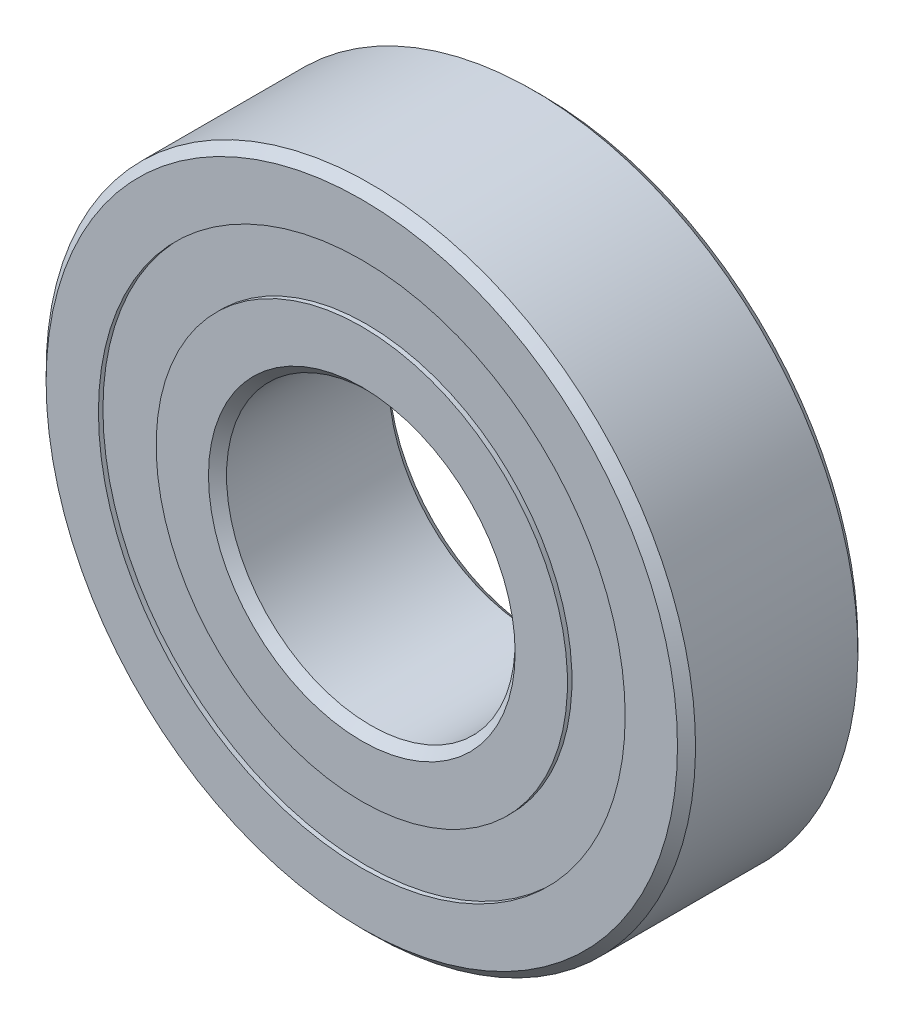
SolidWorks part; units mm, degrees
ref_plane "Front Plane" through (0, 0, 0) normal (0, 0, 1) x (1, 0, 0)
ref_plane "Top Plane" through (0, 0, 0) normal (0, 1, 0) x (1, 0, 0)
ref_plane "Right Plane" through (0, 0, 0) normal (1, 0, 0) x (0, 0, -1)
sketch "Sketch1" plane through (0, 0, 0) normal (0, 0, 1) x (1, 0, 0)
  line L0 (-14.2875, 0) -> (14.2875, 0) construction
  line L1 (-6.35, 0) -> (6.35, 0) construction
  circle A0 centre (0, 0) radius 6.35 construction
  circle A1 centre (0, 0) radius 14.2875 construction
  point P3 (0, 0)
  point P6 (0, 0)
  point P7 (0, -6.35)
  point P11 (0, -14.2875)
  point P12 (0, 6.35)
  point P13 (0, 14.2875)
  dimension "OD" = 28.575
  dimension "ID" = 12.7
sketch "Sketch2" plane through (0, 0, 0) normal (1, 0, 0) x (0, 0, -1)
  line L0 (-3.9687, 14.2875) -> (3.9688, 14.2875) construction
  line L1 (0, 14.2875) -> (0, -14.2875) construction
  line L2 (3.5719, 14.2875) -> (-3.5719, 14.2875)
  line L3 (-3.5719, 14.2875) -> (-3.9687, 13.8906)
  line L4 (-3.9687, 13.8906) -> (-3.9687, 11.5887)
  line L5 (-3.9687, 11.5887) -> (-1.7639, 11.5887)
  line L6 (3.9688, 11.5887) -> (1.7639, 11.5887)
  line L7 (3.9688, 13.8906) -> (3.9688, 11.5887)
  line L8 (3.5719, 14.2875) -> (3.9688, 13.8906)
  line L9 (0, 14.2875) -> (0, 10.3188) construction
  line L10 (0, 10.3188) -> (0, 6.35) construction
  line L11 (0, 14.2875) -> (0, -14.2875) construction
  line L12 (-3.9688, 0) -> (3.9688, 0) construction
  line L13 (3.9688, 6.35) -> (-3.9687, 6.35) construction
  line L14 (-3.9687, 6.35) -> (-3.9687, -6.35) construction
  line L15 (-3.9688, -6.35) -> (3.9687, -6.35) construction
  line L16 (3.9687, 14.2875) -> (3.9687, -14.2875) construction
  arc A0 (-1.7639, 11.5887) -> (1.7639, 11.5887) centre (0, 10.3188) cw
  circle A1 centre (0, 10.3188) radius 2.1735 construction
  point P14 (0, 6.35)
  point P17 (0, 0)
  point P21 (0, 14.2875)
  point P29 (0, 6.35)
  point P30 (0, -6.35)
  dimension "Width" = 7.9375
  dimension "D1" = 45
  dimension "D2" = 0.3969
  dimension "D3" = 3.5278
  dimension "D4" = 1.27
  dimension "For Shaft Diameter" = 12.7
  dimension "For Housing ID" = 28.575
sketch "Sketch3" plane through (0, 0, 0) normal (1, 0, 0) x (0, 0, -1)
  line L0 (3.5719, 14.2875) -> (3.9688, 13.8906) construction
  line L1 (3.9688, 13.8906) -> (3.9688, 11.5887) construction
  line L2 (3.9688, 11.5887) -> (1.7639, 11.5887) construction
  line L3 (-3.9687, 11.5887) -> (-1.7639, 11.5887) construction
  line L4 (-3.9687, 13.8906) -> (-3.9687, 11.5887) construction
  line L5 (-3.5719, 14.2875) -> (-3.9687, 13.8906) construction
  line L6 (3.5719, 14.2875) -> (-3.5719, 14.2875) construction
  line L7 (3.5719, 14.2875) -> (3.9688, 13.8906)
  line L8 (3.9688, 13.8906) -> (3.9688, 11.5887)
  line L9 (3.9688, 11.5887) -> (1.7639, 11.5887)
  line L10 (-3.9687, 11.5887) -> (-1.7639, 11.5887)
  line L11 (-3.9687, 13.8906) -> (-3.9687, 11.5887)
  line L12 (-3.5719, 14.2875) -> (-3.9687, 13.8906)
  line L13 (3.5719, 14.2875) -> (-3.5719, 14.2875)
  arc A0 (1.7639, 11.5887) -> (-1.7639, 11.5887) centre (0, 10.3188) ccw construction
  arc A1 (1.7639, 11.5887) -> (-1.7639, 11.5887) centre (0, 10.3188) ccw
revolve "Revolve1" add sketch "Sketch3" angle 360 about L12
sketch "Sketch4" plane through (0, 0, 0) normal (1, 0, 0) x (0, 0, -1)
  line L0 (0, 14.2875) -> (0, -14.2875) construction
  line L1 (0, 14.2875) -> (0, -14.2875) construction
  line L2 (-3.5719, 6.35) -> (-3.9688, 6.7469)
  line L3 (-3.9688, 6.7469) -> (-3.9688, 9.0488)
  line L5 (-3.9688, 9.0488) -> (-1.7639, 9.0488)
  line L6 (-3.5719, 6.35) -> (3.5719, 6.35)
  line L8 (3.5719, 6.35) -> (3.9688, 6.7469)
  line L10 (3.9688, 6.7469) -> (3.9688, 9.0488)
  line L11 (3.9688, 9.0488) -> (1.7639, 9.0488)
  line L12 (-3.9687, 13.8906) -> (-3.9687, 11.5887) construction
  line L13 (3.5719, 14.2875) -> (3.9688, 13.8906) construction
  line L15 (3.9688, -13.8906) -> (3.9688, 13.8906) construction
  line L16 (3.5719, 14.2875) -> (3.5719, -14.2875) construction
  arc A1 (1.7639, 9.0488) -> (-1.7639, 9.0488) centre (0, 10.3188) cw
  circle A2 centre (0, 10.3188) radius 2.1735 construction
  point P1 (0, 6.35)
revolve "Revolve2" add sketch "Sketch4" angle 360 about L12
sketch "Sketch5" plane through (0, 0, 0) normal (1, 0, 0) x (0, 0, -1)
  line L0 (-2.1735, 10.3188) -> (2.1735, 10.3188)
  arc A2 (-2.1735, 10.3188) -> (2.1735, 10.3188) centre (0, 10.3188) cw
  arc A3 (1.7639, 11.5887) -> (-1.7639, 11.5887) centre (0, 10.3188) ccw construction
revolve "Revolve3" add sketch "Sketch5" angle 360 about L0
pattern_circular "CirPattern1" count 8 over 360 about axis through (0, 0, 0) along (0, 0, 1) of bodies 104
sketch "Sketch6" plane through (0, 0, 0) normal (1, 0, 0) x (0, 0, -1)
  line L0 (-3.9687, 11.5887) -> (-1.7639, 11.5887) construction
  line L1 (-3.7703, 11.5887) -> (-2.1735, 11.5887)
  line L2 (-3.7703, 11.5887) -> (-3.7703, 9.0488)
  line L3 (-3.7703, 9.0488) -> (-2.1735, 9.0488)
  line L4 (-2.1735, 11.5887) -> (-2.1735, 9.0488)
  line L5 (-3.9688, 9.0488) -> (-1.7639, 9.0488) construction
  line L6 (-3.5719, 14.2875) -> (-3.9687, 13.8906) construction
  line L7 (0, 14.2875) -> (0, 6.35) construction
  line L8 (3.7703, 9.0488) -> (2.1735, 9.0488)
  line L9 (2.1735, 11.5887) -> (2.1735, 9.0488)
  line L10 (3.7703, 11.5887) -> (2.1735, 11.5887)
  line L11 (3.7703, 11.5887) -> (3.7703, 9.0488)
  circle A1 centre (0, 10.3188) radius 2.1735 construction
  point P10 (-3.7703, 14.0891)
revolve "Revolve4" add sketch "Sketch6" angle 360 about L12
equation "\"D2@Sketch2\" = \"Width@Sketch2\" * .05"
equation "\"D3@Sketch2\" = \"Width@Sketch2\" / 2.25"
equation "\"D4@Sketch2\" =  (  (  ( \"OD@Sketch1\" - \"Width@Sketch2\" )  / 2 )  / 3.25 )  / 2.5"
